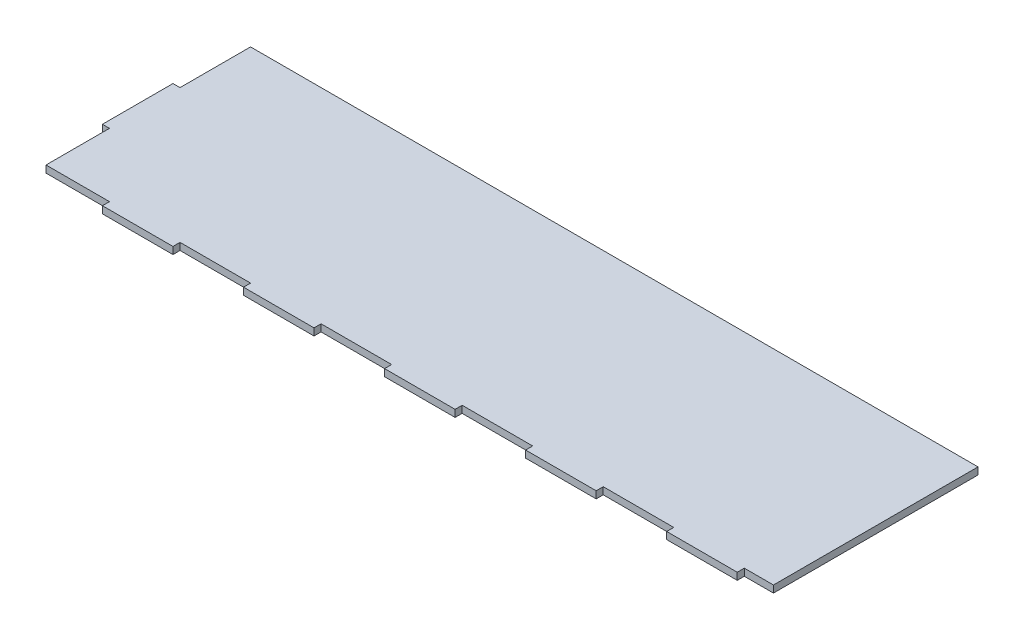
SolidWorks part; units mm, degrees
ref_plane "Front Plane" through (0, 0, 0) normal (0, 0, 1) x (1, 0, 0)
ref_plane "Top Plane" through (0, 0, 0) normal (0, 1, 0) x (1, 0, 0)
ref_plane "Right Plane" through (0, 0, 0) normal (1, 0, 0) x (0, 0, -1)
sketch "Sketch1" plane through (0, 0, 0) normal (0, 1, 0) x (1, 0, 0)
  line L1 (-315, -45) -> (315, -45)
  line L2 (-315, -45) -> (-315, 45)
  line L3 (-315, 45) -> (315, 45)
  line L4 (315, -45) -> (315, 45)
  line L5 (0, 45) -> (0, -45) construction
  line L6 (-315, 0) -> (315, 0) construction
  point P0 (0, 0)
  dimension "D1" = 630
  dimension "D2" = 90
extrude "Boss-Extrude1" add sketch "Sketch1" along normal blind 3
ref_plane "Plane1" through (-255, 0, 0) normal (-1, 0, 0) x (0, 0, 1)
sketch "Sketch3" plane through (0, 3, 0) normal (0, 1, 0) x (1, 0, 0)
  line L0 (-255, 1.65) -> (-255, -1.65) construction
  line L1 (-255, -45) -> (-225, -45)
  line L2 (-255, -45) -> (-255, -42)
  line L3 (-255, -42) -> (-225, -42)
  line L4 (-225, -45) -> (-225, -42)
  line L5 (-315, -45) -> (315, -45) construction
  dimension "D1" = 30
  dimension "D2" = 3
extrude "Cut-Extrude1" cut sketch "Sketch3" against normal blind 3
pattern_linear "LPattern1" count 10 spacing 60 along (1, 0, 0) count 2 spacing 60 along (-1, 0, 0) of "Cut-Extrude1"
ref_plane "Plane2" through (0, 0, -15) normal (0, 0, -1) x (-1, 0, 0)
sketch "Sketch7" plane through (0, 3, 0) normal (0, 1, 0) x (1, 0, 0)
  line L1 (-315, 45) -> (-312, 45)
  line L2 (-315, 45) -> (-315, 15)
  line L3 (-315, 15) -> (-312, 15)
  line L4 (-312, 45) -> (-312, 15)
  dimension "D1" = 30
  dimension "D2" = 3
extrude "Cut-Extrude3" cut sketch "Sketch7" against normal blind 3
ref_plane "Plane3" through (0, 0, 15) normal (0, 0, 1) x (1, 0, 0)
ref_plane "Plane4" through (-312, 3, -45) normal (0, 0, -1) x (-1, 0, 0)
sketch "Sketch13" plane through (0, 3, 0) normal (0, 1, 0) x (1, 0, 0)
  line L0 (-6.6903, -15) -> (6.6903, -15) construction
  line L1 (-315, -42) -> (-312, -42)
  line L2 (-315, -42) -> (-315, -15)
  line L3 (-315, -15) -> (-312, -15)
  line L4 (-312, -42) -> (-312, -15)
  dimension "D1" = 3
extrude "Cut-Extrude4" cut sketch "Sketch13" against normal blind 10
ref_plane "Plane5" through (-2.6, 0, 0) normal (1, 0, 0) x (0, 0, -1)
other "SurfaceCut1"
